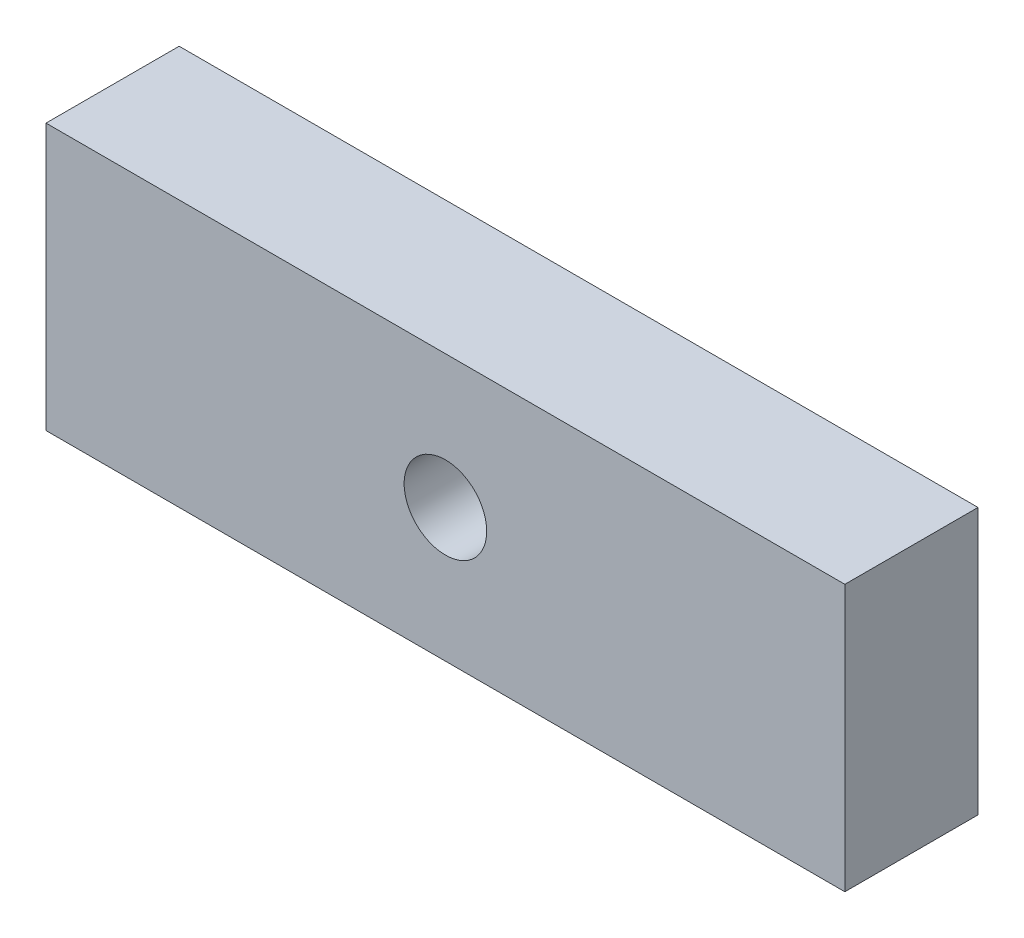
SolidWorks part; units mm, degrees
ref_plane "Front Plane" through (0, 0, 0) normal (0, 0, 1) x (1, 0, 0)
ref_plane "Top Plane" through (0, 0, 0) normal (0, 1, 0) x (1, 0, 0)
ref_plane "Right Plane" through (0, 0, 0) normal (1, 0, 0) x (0, 0, -1)
sketch "Sketch1" plane through (0, 0, 0) normal (0, 0, 1) x (1, 0, 0)
  line L1 (0, 0) -> (60, 0)
  line L2 (0, 0) -> (0, 20)
  line L3 (0, 20) -> (60, 20)
  line L4 (60, 0) -> (60, 20)
  circle A0 centre (30, 10) radius 3.1
extrude "Boss-Extrude1" add sketch "Sketch1" along normal blind 10
